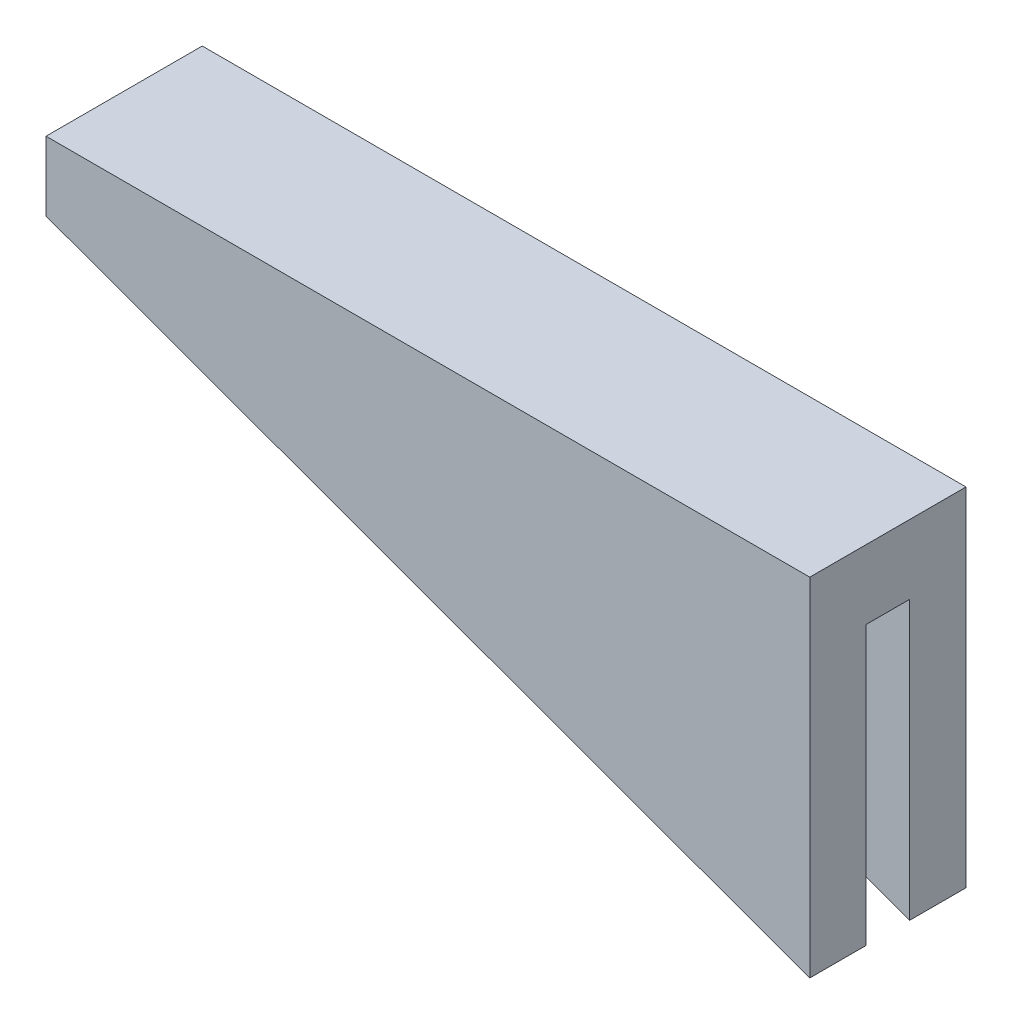
SolidWorks part; units mm, degrees
ref_plane "Front Plane" through (0, 0, 0) normal (0, 0, 1) x (1, 0, 0)
ref_plane "Top Plane" through (0, 0, 0) normal (0, 1, 0) x (1, 0, 0)
ref_plane "Right Plane" through (0, 0, 0) normal (1, 0, 0) x (0, 0, -1)
sketch "Sketch1" plane through (0, 0, 0) normal (0, 0, 1) x (1, 0, 0)
  line L0 (0, 0) -> (88, 0)
  line L1 (88, 0) -> (88, -40)
  line L2 (88, -40) -> (0, -7.9706)
  line L3 (0, -7.9706) -> (0, 0)
  point P6 (0, 0)
  dimension "D1" = 88
  dimension "D2" = 40
  dimension "D3" = 20
extrude "Boss-Extrude1" add sketch "Sketch1" along normal blind 18
sketch "Sketch3" plane through (88, 0, 0) normal (1, 0, 0) x (0, 0, -1)
  line L0 (-18, -40) -> (0, -40) construction
  line L1 (-11.5, -72.0294) -> (-6.5, -72.0294)
  line L2 (-11.5, -72.0294) -> (-11.5, -7.9706)
  line L3 (-11.5, -7.9706) -> (-6.5, -7.9706)
  line L4 (-6.5, -72.0294) -> (-6.5, -7.9706)
  line L5 (-11.5, -72.0294) -> (-6.5, -7.9706) construction
  line L6 (-11.5, -7.9706) -> (-6.5, -72.0294) construction
  line L7 (-18, -7.9706) -> (0, -7.9706) construction
  point P0 (-9, -40)
  dimension "D1" = 5
extrude "Cut-Extrude1" cut sketch "Sketch3" against normal blind 111
